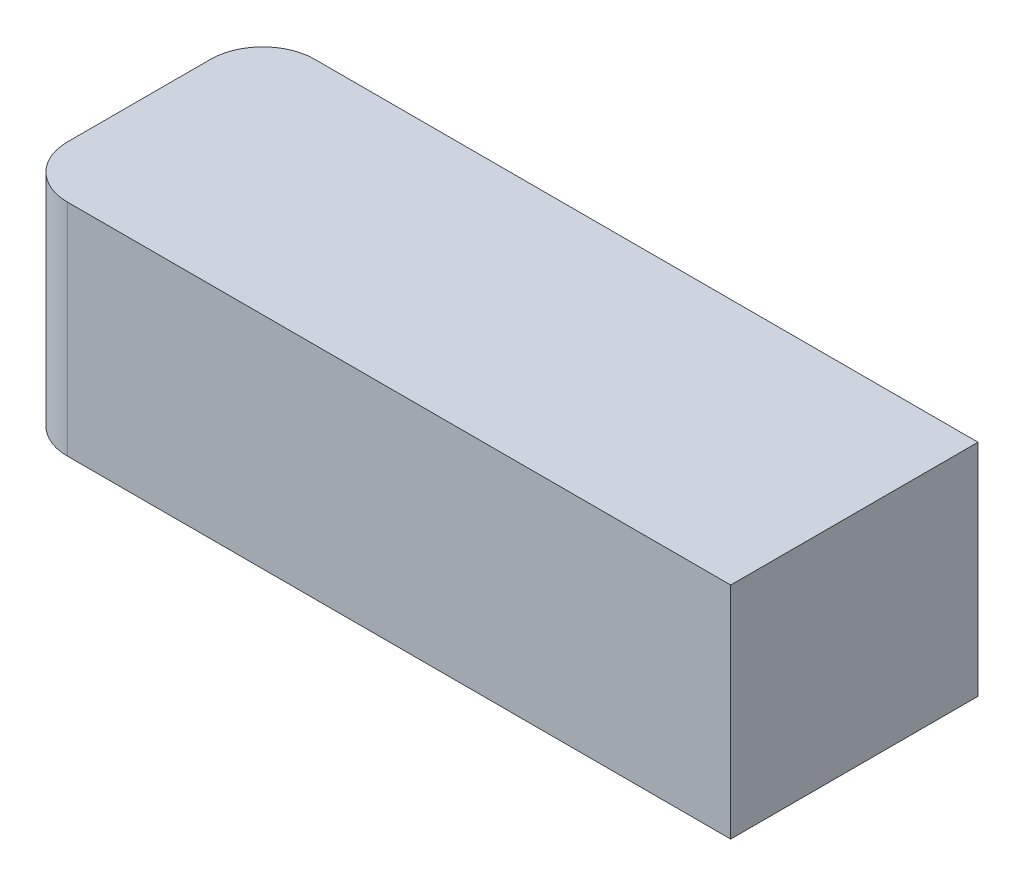
SolidWorks part; units mm, degrees
ref_plane "Front Plane" through (0, 0, 0) normal (0, 0, 1) x (1, 0, 0)
ref_plane "Top Plane" through (0, 0, 0) normal (0, 1, 0) x (1, 0, 0)
ref_plane "Right Plane" through (0, 0, 0) normal (1, 0, 0) x (0, 0, -1)
sketch "Sketch1" plane through (0, 0, 0) normal (0, 0, 1) x (1, 0, 0)
  line L0 (0, 0) -> (137.28, 0)
  line L1 (137.28, 0) -> (137.28, 42.23)
  line L2 (137.28, 42.23) -> (0, 42.23)
  line L3 (0, 42.23) -> (0, 0)
  dimension "D1" = 137.28
  dimension "D2" = 42.23
extrude "Boss-Extrude1" add sketch "Sketch1" along normal blind 47.46
fillet "Fillet1" radius 10 2 edges at (0, 21.115, 47.46) (0, 21.115, 0)
